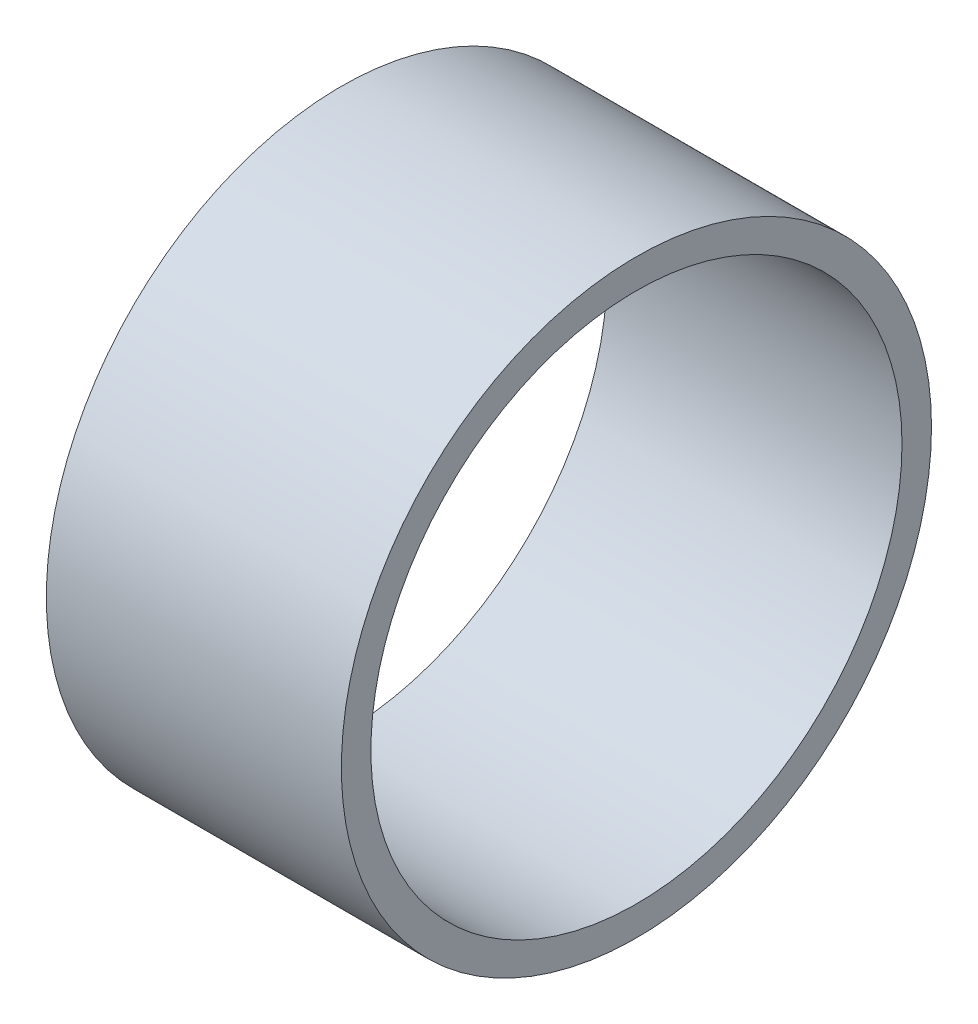
SolidWorks part; units mm, degrees
material "Commercialement pur CP-Ti UNS R50400 (SS)"
ref_plane "Plan de face" through (0, 0, 0) normal (0, 0, 1) x (1, 0, 0)
ref_plane "Plan de dessus" through (0, 0, 0) normal (0, 1, 0) x (1, 0, 0)
ref_plane "Plan de droite" through (0, 0, 0) normal (1, 0, 0) x (0, 0, -1)
sketch "Esquisse1" plane through (0, 0, 0) normal (1, 0, 0) x (0, 0, -1)
  circle A0 centre (0, 0) radius 100
  circle A1 centre (0, 0) radius 90
  dimension "D1" = 200
  dimension "D2" = 180
extrude "Boss.-Extru.1" add sketch "Esquisse1" along normal blind 100
